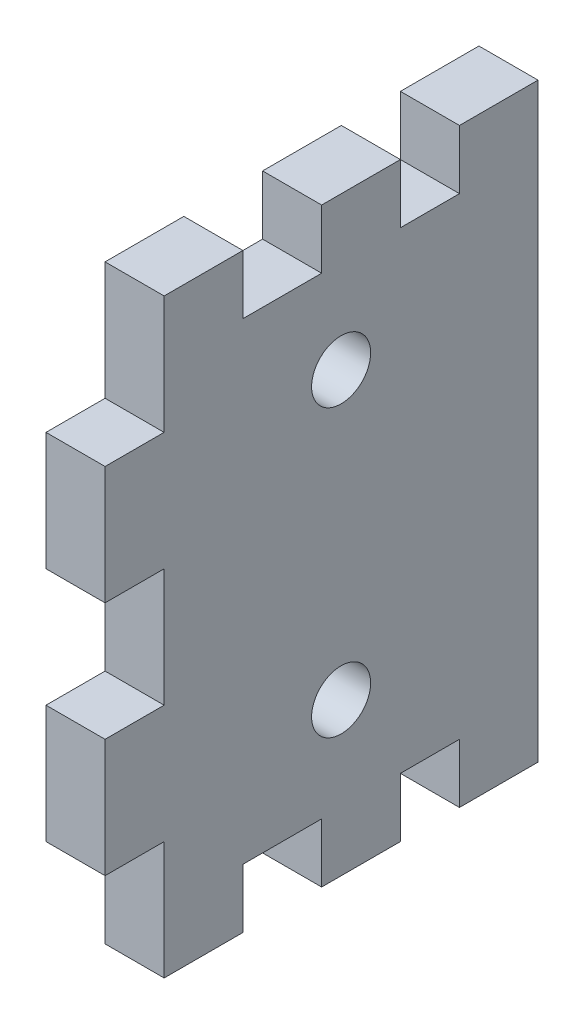
SolidWorks part; units mm, degrees
ref_plane "Front Plane" through (0, 0, 0) normal (0, 0, 1) x (1, 0, 0)
ref_plane "Top Plane" through (0, 0, 0) normal (0, 1, 0) x (1, 0, 0)
ref_plane "Right Plane" through (0, 0, 0) normal (1, 0, 0) x (0, 0, -1)
sketch "Sketch1" plane through (0, 0, 0) normal (1, 0, 0) x (0, 0, -1)
  line L0 (0, -29.1771) -> (-3.9885, -29.1771)
  line L1 (-18.9885, -29.1771) -> (-18.9885, -23.1771)
  line L2 (-18.9885, -23.1771) -> (-21.9885, -23.1771)
  line L3 (-21.9885, -23.1771) -> (-21.9885, -17.1771)
  line L4 (0, -29.1771) -> (0, 0.8229)
  line L5 (-3.9885, 0.8229) -> (-3.9885, -14.1771) construction
  line L6 (-21.9885, -17.1771) -> (-18.9885, -17.1771)
  line L7 (-14.9885, -2.1771) -> (-14.9885, 0.8229)
  line L8 (-18.9885, 0.8229) -> (-14.9885, 0.8229)
  line L9 (-10.9885, 0.8229) -> (-10.9885, -2.1771)
  line L10 (-10.9885, -29.1771) -> (-6.9885, -29.1771)
  line L11 (-10.9885, -29.1771) -> (-10.9885, -26.1771)
  line L12 (-10.9885, 0.8229) -> (-6.9885, 0.8229)
  line L13 (0, -14.1771) -> (-3.9885, -14.1771) construction
  line L14 (-14.9885, -26.1771) -> (-14.9885, -29.1771)
  line L15 (-18.9885, -29.1771) -> (-14.9885, -29.1771)
  line L16 (-10.9885, -2.1771) -> (-14.9885, -2.1771)
  line L17 (-10.9885, -26.1771) -> (-14.9885, -26.1771)
  line L18 (-18.9885, -17.1771) -> (-18.9885, -11.1771)
  line L19 (-6.9885, 0.8229) -> (-6.9885, -2.1771)
  line L20 (-6.9885, -2.1771) -> (-3.9885, -2.1771)
  line L21 (-6.9885, -29.1771) -> (-6.9885, -26.1771)
  line L22 (-6.9885, -26.1771) -> (-3.9885, -26.1771)
  line L23 (-3.9885, -26.1771) -> (-3.9885, -29.1771)
  line L24 (0, 0.8229) -> (-3.9885, 0.8229)
  line L25 (-3.9885, -2.1771) -> (-3.9885, 0.8229)
  line L26 (-18.9885, -11.1771) -> (-21.9885, -11.1771)
  line L27 (-21.9885, -11.1771) -> (-21.9885, -5.1771)
  line L28 (-21.9885, -5.1771) -> (-18.9885, -5.1771)
  line L29 (-18.9885, -5.1771) -> (-18.9885, 0.8229)
  circle A0 centre (-10, -6.9171) radius 1.5
  circle A1 centre (-10, -21.4371) radius 1.5
  dimension "D1" = 3
  dimension "D2" = 7.26
  dimension "D3" = 6
  dimension "D4" = 3
  dimension "D5" = 3
  dimension "D6" = 3
  dimension "D7" = 3
  dimension "D8" = 4
  dimension "D9" = 10
  dimension "D10" = 4
  dimension "D11" = 4
  dimension "D12" = 3
  dimension "D13" = 3
  dimension "D14" = 6
  dimension "D15" = 6
  dimension "D16" = 6
  dimension "D17" = 6
  dimension "D18" = 3
  dimension "D19" = 30
extrude "Boss-Extrude1" add sketch "Sketch1" along normal blind 3
